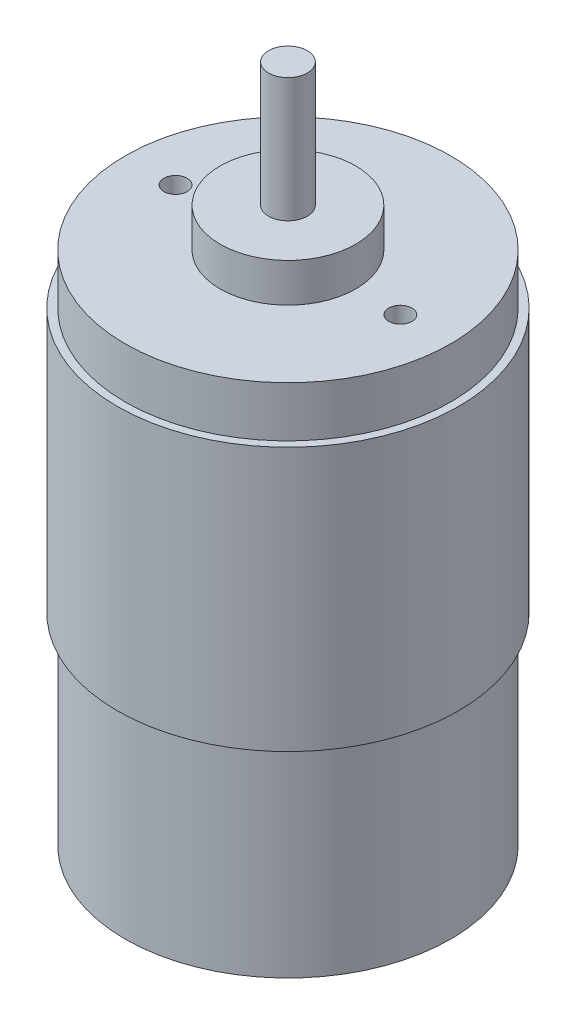
SolidWorks part; units mm, degrees
ref_plane "前视基准面" through (0, 0, 0) normal (0, 0, 1) x (1, 0, 0)
ref_plane "上视基准面" through (0, 0, 0) normal (0, 1, 0) x (1, 0, 0)
ref_plane "右视基准面" through (0, 0, 0) normal (1, 0, 0) x (0, 0, -1)
sketch "草图1" plane through (0, 0, 0) normal (0, 0, 1) x (1, 0, 0)
  line L0 (0, 120.5763) -> (0, 0) construction
  line L1 (0, 98) -> (2.5, 98)
  line L2 (2.5, 98) -> (2.5, 82)
  line L3 (2.5, 82) -> (8.75, 82)
  line L4 (8.75, 82) -> (8.75, 77)
  line L5 (8.75, 77) -> (21, 77)
  line L6 (21, 77) -> (21, 70.5)
  line L7 (21, 70.5) -> (22, 70.5)
  line L8 (22, 70.5) -> (22, 36.5)
  line L9 (22, 36.5) -> (21, 36.5)
  line L10 (21, 36.5) -> (21, 10.5)
  line L11 (21, 10.5) -> (7.5, 10.5)
  line L12 (7.5, 10.5) -> (7.5, 5)
  line L13 (7.5, 5) -> (5, 5)
  line L14 (5, 5) -> (5, 0)
  line L15 (5, 0) -> (0, 0)
  line L16 (0, 98) -> (0, 0)
  dimension "D1" = 2.5
  dimension "D2" = 8.75
  dimension "D3" = 21
  dimension "D4" = 22
  dimension "D5" = 7.5
  dimension "D6" = 5
  dimension "D7" = 16
  dimension "D8" = 5
  dimension "D9" = 6.5
  dimension "D10" = 34
  dimension "D11" = 26
  dimension "D12" = 5
  dimension "D13" = 98
revolve "旋转1" add sketch "草图1" angle 360 about L0
sketch "草图2" plane through (0, 77, 0) normal (0, 1, 0) x (1, 0, 0)
  line L0 (0, 0) -> (37.3714, 0) construction
  line L1 (0, 23.1004) -> (0, 0) construction
  circle A0 centre (14.5, 0) radius 1.5
  circle A1 centre (-14.5, 0) radius 1.5
  dimension "D2" = 3
  dimension "D1" = 29
extrude "切除-拉伸1" cut sketch "草图2" against normal blind 10
